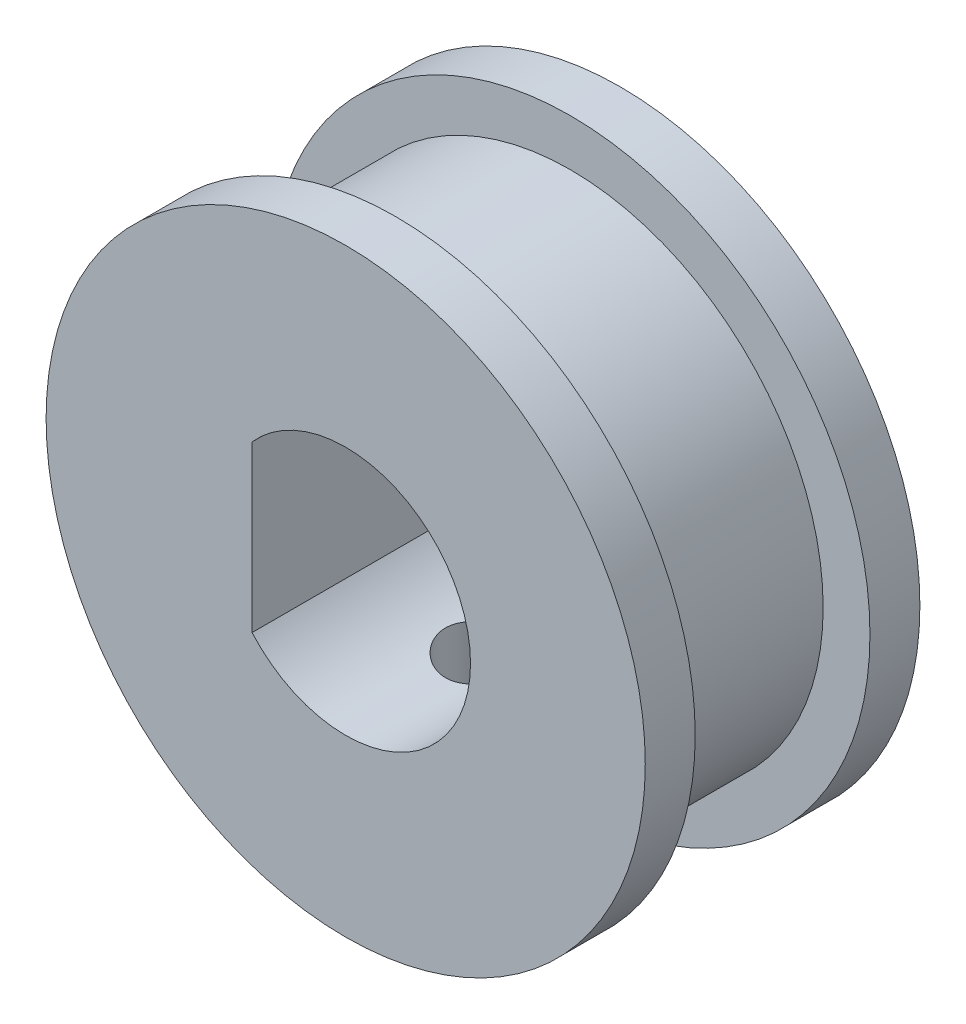
SolidWorks part; units mm, degrees
material "6061 合金"
ref_plane "前视基准面" through (0, 0, 0) normal (0, 0, 1) x (1, 0, 0)
ref_plane "上视基准面" through (0, 0, 0) normal (0, 1, 0) x (1, 0, 0)
ref_plane "右视基准面" through (0, 0, 0) normal (1, 0, 0) x (0, 0, -1)
sketch "草图1" plane through (0, 0, 0) normal (0, 0, 1) x (1, 0, 0)
  circle A0 centre (0, 0) radius 10.125
extrude "凸台-拉伸1" add sketch "草图1" along normal mid plane 7
sketch "草图2" plane through (0, 0, 3.5) normal (0, 0, 1) x (1, 0, 0)
  circle A0 centre (0, 0) radius 12
extrude "凸台-拉伸2" add sketch "草图2" along normal blind 2
mirror "镜向1" about plane through (0, 0, 0) normal (0, 0, 1) of "凸台-拉伸2"
sketch "草图3" plane through (0, 0, 5.5) normal (0, 0, 1) x (1, 0, 0)
  line L0 (0, 0) -> (-3.75, 0) construction
  line L2 (-3.75, 3.3072) -> (-3.75, -3.3072)
  arc A1 (-3.75, -3.3072) -> (-3.75, 3.3072) centre (0, 0) ccw
extrude "切除-拉伸1" cut sketch "草图3" against normal through all
sketch "草图4" plane through (0, 0, 0) normal (0, 1, 0) x (1, 0, 0)
  circle A0 centre (0, 0) radius 1.5
extrude "切除-拉伸2" cut sketch "草图4" against normal through all
